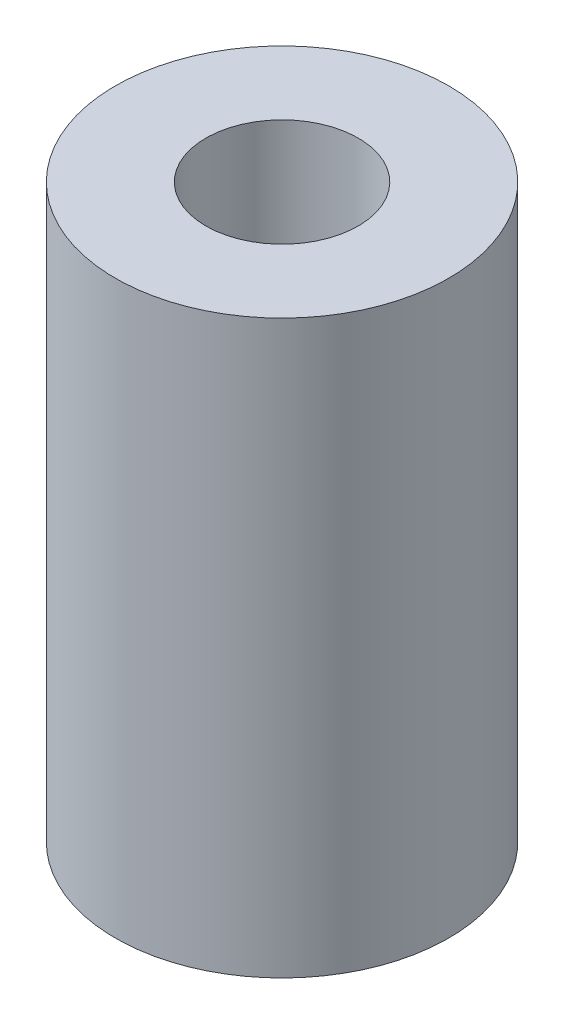
SolidWorks part; units mm, degrees
material "Brass"
ref_plane "Front Plane" through (0, 0, 0) normal (0, 0, 1) x (1, 0, 0)
ref_plane "Top Plane" through (0, 0, 0) normal (0, 1, 0) x (1, 0, 0)
ref_plane "Right Plane" through (0, 0, 0) normal (1, 0, 0) x (0, 0, -1)
sketch "Sketch1" plane through (0, 0, 0) normal (0, 0, 1) x (1, 0, 0)
  line L0 (0, 0) -> (0, 22.592) construction
  line L2 (0, 0) -> (-1.75, 0)
  line L3 (0, 0) -> (0, 6)
  line L4 (0, 6) -> (-1.75, 6)
  line L5 (-1.75, 0) -> (-1.75, 6)
  dimension "D1" = 6
  dimension "D2" = 3.5
revolve "Revolve1" add sketch "Sketch1" angle 360 about L0
hole_wizard "M2x0.4 Tapped Hole1" positions "Sketch4" profile "Sketch3" tap size "M2x0.4" standard "ANSI Metric" end condition up to next
sketch "Sketch4" plane through (0, 6, 0) normal (0, 1, 0) x (-1, 0, 0)
  point P0 (0, 0)
sketch "Sketch3" plane through (0, 6, 0) normal (1, 0, 0) x (0, 0, 1)
  line L0 (0, 0) -> (0, 6)
  line L1 (0, 6) -> (0.8, 6)
  line L2 (0.8, 6) -> (0.8, 0)
  line L5 (0.8, 0) -> (0, 0)
  line L11 (0, -6.35) -> (0, 107.95) construction
  dimension "Thru Tap Drill Dia." = 1.6
  dimension "Thru Tap Drill Depth" = 6
cosmetic thread "Hole Thread1" parameters "D2"=2
